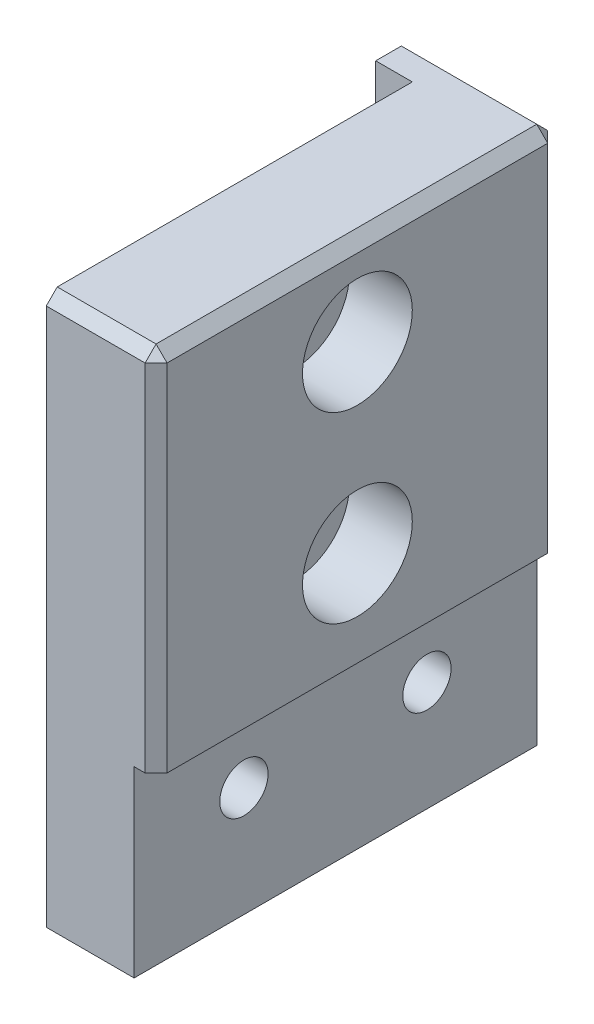
SolidWorks part; units mm, degrees
material "Alumina"
ref_plane "Front Plane" through (0, 0, 0) normal (0, 0, 1) x (1, 0, 0)
ref_plane "Top Plane" through (0, 0, 0) normal (0, 1, 0) x (1, 0, 0)
ref_plane "Right Plane" through (0, 0, 0) normal (1, 0, 0) x (0, 0, -1)
sketch "Sketch1" plane through (0, 0, 0) normal (0, 0, 1) x (1, 0, 0)
  line L5 (0, 0) -> (110, 0)
  line L7 (20, 20) -> (110, 20)
  line L8 (110, 0) -> (110, 20)
  line L10 (0, 0) -> (0, 70)
  line L11 (0, 70) -> (20, 70)
  line L12 (20, 20) -> (20, 70)
  dimension "D1" = 110
  dimension "D2" = 70
  dimension "D3" = 20
  dimension "D4" = 20
extrude "Boss-Extrude1" add sketch "Sketch1" along normal blind 55
sketch "Sketch2" plane through (0, 0, 0) normal (-1, 0, 0) x (0, 0, 1)
  line L0 (55, 0) -> (0, 0) construction
  line L1 (55, 70) -> (50, 70)
  line L2 (55, 70) -> (55, 0)
  line L3 (55, 0) -> (50, 0)
  line L4 (50, 70) -> (50, 0)
  line L6 (0, 70) -> (5, 70)
  line L7 (0, 70) -> (0, 0)
  line L8 (0, 0) -> (5, 0)
  line L9 (5, 70) -> (5, 0)
  dimension "D1" = 5
  dimension "D2" = 5
extrude "Boss-Extrude2" add sketch "Sketch2" along normal blind 5
hole_wizard "M5 Tapped Hole1" positions "Sketch3" profile "Sketch4" tap size "M5" standard "DIN"
sketch "Sketch3" plane through (0, 0, 55) normal (0, 0, 1) x (1, 0, 0)
  line L0 (110, 0) -> (110, 20) construction
  line L1 (110, 20) -> (20, 20) construction
  point P0 (100, 12.5)
  point P2 (80, 12.5)
  point P4 (60, 12.5)
  point P6 (40, 12.5)
  dimension "D1" = 10
  dimension "D2" = 20
  dimension "D3" = 20
  dimension "D4" = 20
  dimension "D6" = 7.5
sketch "Sketch4" plane through (100, 12.5, 55) normal (1, 0, 0) x (0, -1, 0)
  line L0 (0, 0) -> (0, 15.2618)
  line L1 (0, 15.2618) -> (2.1, 14)
  line L2 (2.1, 14) -> (2.1, 0)
  line L5 (2.1, 0) -> (0, 0)
  line L10 (0, 15.2618) -> (-2.1, 14) construction
  line L11 (0, -6.35) -> (0, 107.95) construction
  dimension "Tap Drill Dia." = 4.2
  dimension "Tap Drill Depth" = 14
  dimension "Drill Angle" = 118
cosmetic thread "Hole Thread2" parameters "D1"=10, "D2"=5
cosmetic thread "Hole Thread3" parameters "D1"=10, "D2"=5
cosmetic thread "Hole Thread4" parameters "D1"=10, "D2"=5
cosmetic thread "Hole Thread5" parameters "D1"=10, "D2"=5
ref_plane "Plane1" through (0, 0, 27.5) normal (0, 0, 1) x (1, 0, 0)
mirror "Mirror1" about plane through (0, 0, 27.5) normal (0, 0, 1) of "M5 Tapped Hole1"
sketch "Sketch8" plane through (0, 0, 55) normal (0, 0, 1) x (1, 0, 0)
  line L0 (20, 20) -> (20, 70) construction
  line L1 (20, 36.8167) -> (124.5642, 36.8167)
  line L2 (20, 36.8167) -> (20, -9.7457)
  line L3 (20, -9.7457) -> (124.5642, -9.7457)
  line L4 (124.5642, 36.8167) -> (124.5642, -9.7457)
extrude "Cut-Extrude1" cut sketch "Sketch8" against normal blind 87
sketch "Sketch9" plane through (0, 0, 0) normal (0, -1, 0) x (1, 0, 0)
  line L0 (-5, 55) -> (-5, 50)
  line L1 (-5, 50) -> (0, 50)
  line L2 (0, 50) -> (0, 5)
  line L3 (0, 5) -> (-5, 5)
  line L4 (-5, 5) -> (-5, 0)
  line L5 (-5, 0) -> (20, 0)
  line L6 (20, 0) -> (20, 55)
  line L7 (20, 55) -> (-5, 55)
extrude "Boss-Extrude3" add sketch "Sketch9" along normal blind 5
sketch "Sketch10" plane through (20, 0, 0) normal (1, 0, 0) x (0, 0, -1)
  line L0 (-55, -5) -> (-55, 70) construction
  line L1 (-55, 20) -> (0, 20)
  line L2 (-55, 20) -> (-55, 0)
  line L3 (-55, 0) -> (0, 0)
  line L4 (0, 20) -> (0, 0)
  line L5 (0, -5) -> (0, 70) construction
  line L6 (0, -5) -> (-55, -5) construction
  dimension "D1" = 5
  dimension "D2" = 20
extrude "Cut-Extrude2" cut sketch "Sketch10" against normal blind 3
hole_wizard "CBORE for M6 Hex Socket Head Cap Screw1" positions "Sketch11" profile "Sketch12" counterbore size "M6" standard "DIN" end condition through all
sketch "Sketch11" plane through (0, 0, 0) normal (-1, 0, 0) x (0, 0, 1)
  line L0 (50, -5) -> (5, -5) construction
  line L1 (0, 70) -> (0, -5) construction
  line L2 (55, -5) -> (55, 70) construction
  point P0 (15, 10)
  point P2 (40, 10)
  dimension "D1" = 15
  dimension "D2" = 15
  dimension "D3" = 15
  dimension "D4" = 15
sketch "Sketch12" plane through (0, 10, 15) normal (0, 1, 0) x (0, 0, 1)
  line L0 (0, 0) -> (0, 20)
  line L1 (0, 20) -> (3.3, 20)
  line L3 (3.3, 20) -> (3.3, 6.4)
  line L4 (3.3, 6.4) -> (5.5, 6.4)
  line L5 (5.5, 6.4) -> (5.5, 0)
  line L7 (5.5, 0) -> (0, 0)
  line L11 (0, -6.35) -> (0, 107.95) construction
  dimension "Thru Hole Dia." = 6.6
  dimension "Thru Hole Depth" = 20
  dimension "C'Bore Dia." = 11
  dimension "C'Bore Depth" = 6.4
sketch "Sketch13" plane through (17, 0, 0) normal (1, 0, 0) x (0, 0, -1)
  line L1 (-55, 20) -> (0, 20)
  line L2 (-55, 20) -> (-55, 0)
  line L3 (-55, 0) -> (0, 0)
  line L4 (0, 20) -> (0, 0)
extrude "Cut-Extrude3" cut sketch "Sketch13" against normal blind 5
sketch "Sketch14" plane through (0, 70, 0) normal (0, 1, 0) x (1, 0, 0)
  line L0 (20, -55) -> (-5, -55) construction
  line L1 (20, 0) -> (15, 0)
  line L2 (20, 0) -> (20, -55)
  line L3 (20, -55) -> (15, -55)
  line L4 (15, 0) -> (15, -55)
  dimension "D1" = 5
extrude "Cut-Extrude4" cut sketch "Sketch14" against normal blind 210
sketch "Sketch15" plane through (0, 0, 55) normal (0, 0, 1) x (1, 0, 0)
  line L0 (15, -5) -> (-5, -5) construction
  line L1 (15, 0) -> (12, 0)
  line L2 (15, 0) -> (15, -5)
  line L3 (15, -5) -> (12, -5)
  line L4 (12, 0) -> (12, -5)
extrude "Cut-Extrude5" cut sketch "Sketch15" against normal blind 210
hole_wizard "CBORE for M8 Hex Socket Head Cap Screw1" positions "Sketch16" profile "Sketch17" counterbore size "M8" standard "DIN" end condition through all
sketch "Sketch16" plane through (15, 0, 0) normal (1, 0, 0) x (0, 0, -1)
  line L0 (0, 70) -> (-55, 70) construction
  point P0 (-27.5, 58)
  point P2 (-27.5, 33)
  dimension "D1" = 12
  dimension "D2" = 25
sketch "Sketch17" plane through (15, 58, 27.5) normal (0, 1, 0) x (0, 0, -1)
  line L0 (0, 0) -> (0, 20)
  line L1 (0, 20) -> (4.5, 20)
  line L3 (4.5, 20) -> (4.5, 8.6)
  line L4 (4.5, 8.6) -> (7.5, 8.6)
  line L5 (7.5, 8.6) -> (7.5, 0)
  line L7 (7.5, 0) -> (0, 0)
  line L11 (0, -6.35) -> (0, 107.95) construction
  dimension "Thru Hole Dia." = 9
  dimension "Thru Hole Depth" = 20
  dimension "C'Bore Dia." = 15
  dimension "C'Bore Depth" = 8.6
sketch "Sketch18" plane through (0, 0, 50) normal (0, 0, -1) x (-1, 0, 0)
  line L1 (5, 70) -> (0, 70)
  line L2 (5, 70) -> (5, -5)
  line L3 (5, -5) -> (0, -5)
  line L4 (0, 70) -> (0, -5)
extrude "Cut-Extrude6" cut sketch "Sketch18" against normal blind 210
chamfer "Chamfer1" distance 1.5 angle 45 5 edges at (5, 70, 0) (15, 45, 0) (15, 70, 27.5) (15, 45, 55) (7.5, 70, 55)
